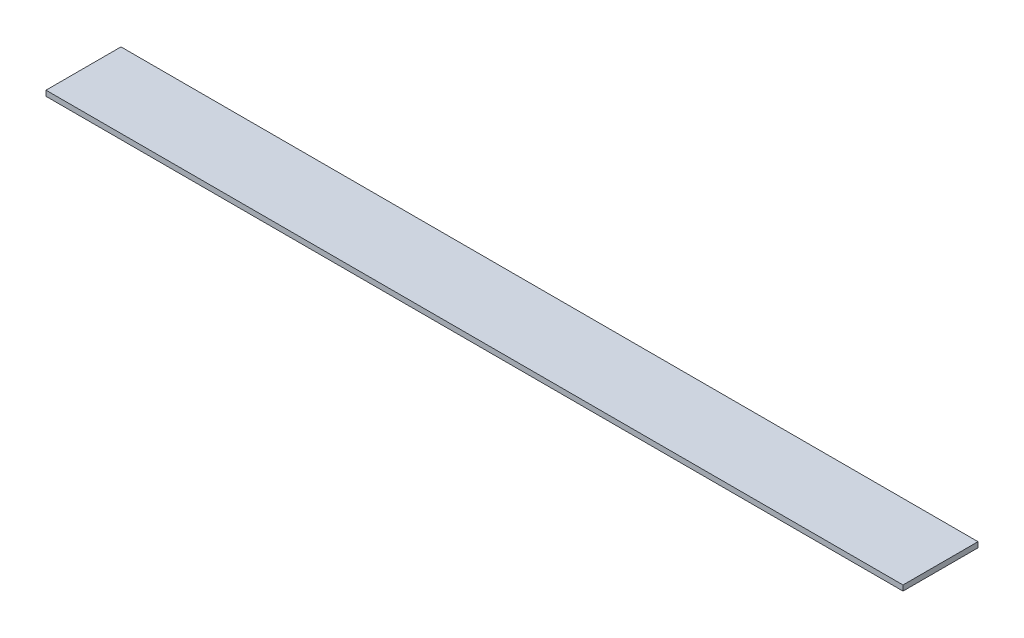
SolidWorks part; units mm, degrees
material "A-Glass Fiber"
ref_plane "Front Plane" through (0, 0, 0) normal (0, 0, 1) x (1, 0, 0)
ref_plane "Top Plane" through (0, 0, 0) normal (0, 1, 0) x (1, 0, 0)
ref_plane "Right Plane" through (0, 0, 0) normal (1, 0, 0) x (0, 0, -1)
sketch "Sketch2" plane through (0, 0, 0) normal (0, 1, 0) x (1, 0, 0)
  line L1 (-0.8, 0.07) -> (0.8, 0.07)
  line L2 (-0.8, 0.07) -> (-0.8, -0.07)
  line L3 (-0.8, -0.07) -> (0.8, -0.07)
  line L4 (0.8, 0.07) -> (0.8, -0.07)
  line L5 (-0.8, 0.07) -> (0.8, -0.07) construction
  line L6 (-0.8, -0.07) -> (0.8, 0.07) construction
  point P0 (0, 0)
  dimension "D1" = 1.6
  dimension "D2" = 0.14
extrude "Boss-Extrude1" add sketch "Sketch2" along normal blind 0.01
